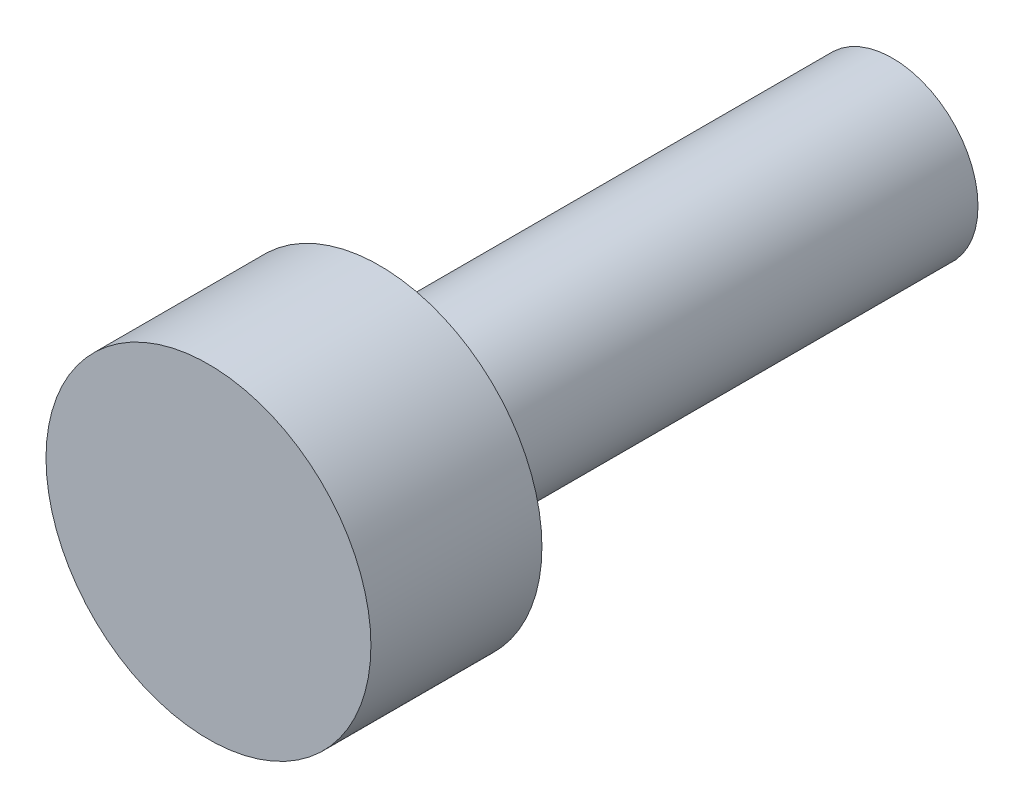
SolidWorks part; units mm, degrees
ref_plane "Front Plane" through (0, 0, 0) normal (0, 0, 1) x (1, 0, 0)
ref_plane "Top Plane" through (0, 0, 0) normal (0, 1, 0) x (1, 0, 0)
ref_plane "Right Plane" through (0, 0, 0) normal (1, 0, 0) x (0, 0, -1)
sketch "Sketch1" plane through (0, 0, 0) normal (0, 0, 1) x (1, 0, 0)
  circle A0 centre (0, 0) radius 1
extrude "Thread_Envelope" add sketch "Sketch1" along normal blind 6 from offset 6
sketch "Sketch2" plane through (0, 0, 0) normal (0, 0, 1) x (1, 0, 0)
  circle A0 centre (0, 0) radius 1.9
extrude "Head_Envelope" add sketch "Sketch2" along normal blind 2
